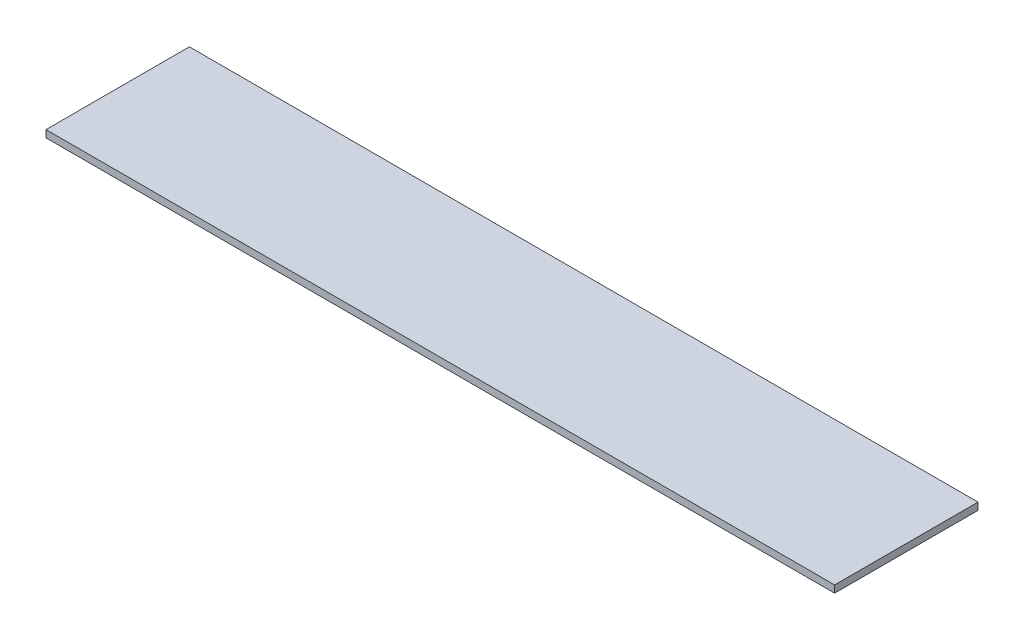
SolidWorks part; units mm, degrees
ref_plane "Front Plane" through (0, 0, 0) normal (0, 0, 1) x (1, 0, 0)
ref_plane "Top Plane" through (0, 0, 0) normal (0, 1, 0) x (1, 0, 0)
ref_plane "Right Plane" through (0, 0, 0) normal (1, 0, 0) x (0, 0, -1)
sketch "Sketch1" plane through (0, 0, 0) normal (0, 1, 0) x (1, 0, 0)
  line L1 (0, 0) -> (110, 0)
  line L2 (0, 0) -> (0, 20)
  line L3 (0, 20) -> (110, 20)
  line L4 (110, 0) -> (110, 20)
  dimension "D1" = 110
  dimension "D2" = 20
extrude "Boss-Extrude1" add sketch "Sketch1" along normal blind 1
sketch "Sketch2" plane through (0, 1, 0) normal (0, 1, 0) x (1, 0, 0)
  text T0 "LTE Full Band PCB Antenna"
